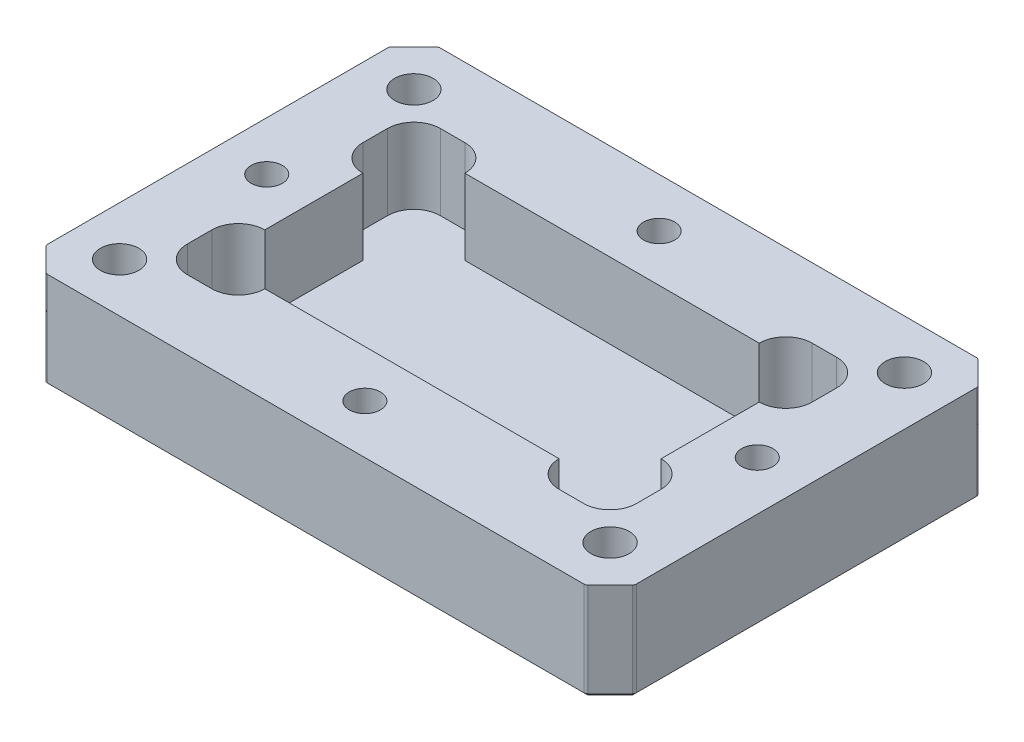
SolidWorks part; units mm, degrees
ref_plane "Front Plane" through (0, 0, 0) normal (0, 0, 1) x (1, 0, 0)
ref_plane "Top Plane" through (0, 0, 0) normal (0, 1, 0) x (1, 0, 0)
ref_plane "Right Plane" through (0, 0, 0) normal (1, 0, 0) x (0, 0, -1)
sketch "Sketch1" plane through (0, 0, 0) normal (0, 1, 0) x (1, 0, 0)
  line L1 (-38.1, 25.4) -> (38.1, 25.4)
  line L2 (-38.1, 25.4) -> (-38.1, -25.4)
  line L3 (-38.1, -25.4) -> (38.1, -25.4)
  line L4 (38.1, 25.4) -> (38.1, -25.4)
  line L5 (-38.1, 25.4) -> (38.1, -25.4) construction
  line L6 (-38.1, -25.4) -> (38.1, 25.4) construction
  point P0 (0, 0)
  dimension "D1" = 76.2
  dimension "D2" = 50.8
extrude "Boss-Extrude1" add sketch "Sketch1" along normal blind 12.7
sketch "Sketch2" plane through (0, 12.7, 0) normal (0, 1, 0) x (1, 0, 0)
  line L1 (-25.654, 12.954) -> (25.654, 12.954)
  line L2 (-25.654, 12.954) -> (-25.654, -12.954)
  line L3 (-25.654, -12.954) -> (25.654, -12.954)
  line L4 (25.654, 12.954) -> (25.654, -12.954)
  line L5 (-25.654, 12.954) -> (25.654, -12.954) construction
  line L6 (-25.654, -12.954) -> (25.654, 12.954) construction
  point P0 (0, 0)
  dimension "D1" = 51.308
  dimension "D2" = 25.908
extrude "Cut-Extrude1" cut sketch "Sketch2" against normal blind 9.779
sketch "Sketch3" plane through (0, 12.7, 0) normal (0, 1, 0) x (1, 0, 0)
  line L0 (25.654, 12.954) -> (-25.654, 12.954) construction
  line L2 (-25.654, 12.954) -> (-25.654, -12.954) construction
  line L3 (-22.479, 16.383) -> (-25.654, 16.383)
  line L4 (-29.083, 12.954) -> (-29.083, 9.779)
  line L6 (-23.2293, 7.3543) -> (-20.0543, 10.5293)
  line L7 (25.654, 12.954) -> (-25.654, 12.954) construction
  arc A0 (-20.0543, 10.5293) -> (-22.479, 16.383) centre (-22.479, 12.954) ccw
  arc A1 (-29.083, 9.779) -> (-23.2293, 7.3543) centre (-25.654, 9.779) ccw
  arc A2 (-25.654, 16.383) -> (-29.083, 12.954) centre (-25.654, 12.954) ccw
  dimension "D1" = 3.429
  dimension "D2" = 3.175
  dimension "D3" = 3.175
extrude "Cut-Extrude2" cut sketch "Sketch3" against normal up to surface (9.779 mm away) up to face at (0, 2.921, 0)
mirror "Mirror1" about plane through (0, 0, 0) normal (0, 0, 1) of "Cut-Extrude2"
mirror "Mirror2" about plane through (0, 0, 0) normal (1, 0, 0) of "Mirror1", "Cut-Extrude2"
hole_wizard "CBORE for #10 Socket Head Cap Screw" positions "Sketch4" profile "Sketch5" counterbore size "#10" standard "ANSI Inch" end condition through all
sketch "Sketch4" plane through (-13.3951, 0, 69.6344) normal (0, -1, 0) x (1, 0, 0)
  point P0 (-18.3549, -50.5844)
  point P2 (45.1451, -50.5844)
  point P4 (45.1451, -88.6844)
  point P6 (-18.3549, -88.6844)
sketch "Sketch5" plane through (-31.75, 0, 19.05) normal (1, 0, 0) x (0, 0, -1)
  line L0 (0, 0) -> (0, 12.7)
  line L1 (0, 12.7) -> (2.4892, 12.7)
  line L2 (2.4892, 12.7) -> (2.4892, 5.08)
  line L3 (2.4892, 5.08) -> (4.445, 5.08)
  line L4 (4.445, 5.08) -> (4.445, 0)
  line L5 (4.445, 0) -> (0, 0)
  line L6 (0, -6.35) -> (0, 107.95) construction
  dimension "Thru Hole Dia." = 4.9784
  dimension "Thru Hole Depth" = 12.7
  dimension "C'Bore Dia." = 8.89
  dimension "C'Bore Depth" = 5.08
chamfer "Chamfer1" distance 3.175 angle 45 4 edges at (38.1, 6.35, 25.4) (38.1, 6.35, -25.4) (-38.1, 6.35, 25.4) (-38.1, 6.35, -25.4)
fillet "Fillet1" radius 0.508 8 edges at (-38.1, 6.35, -22.225) (-34.925, 6.35, -25.4) (34.925, 6.35, -25.4) (38.1, 6.35, -22.225) (38.1, 6.35, 22.225) (34.925, 6.35, 25.4) (-38.1, 6.35, 22.225) (-34.925, 6.35, 25.4)
chamfer "Chamfer2" distance 0.508 angle 45 16 edges at (36.5125, 0, -23.8125) (38.1, 0, 0) (36.5125, 0, 23.8125) (0, 0, 25.4) (-36.5125, 0, 23.8125) (-38.1, 0, 0) (-36.5125, 0, -23.8125) (0, 0, -25.4) (34.909, 0, 25.3613) (-34.909, 0, 25.3613) (38.0613, 0, 22.209) (-38.0613, 0, 22.209) (38.0613, 0, -22.209) (-38.0613, 0, -22.209) (34.909, 0, -25.3613) (-34.909, 0, -25.3613)
hole_wizard "#10-32 Tapped Hole1" positions "Sketch6" profile "Sketch7" tap size "#10-32" standard "ANSI Inch" end condition through all
sketch "Sketch6" plane through (0, 0, 0) normal (0, -1, 0) x (-1, 0, 0)
  line L0 (0, 19.05) -> (0, -19.05)
  line L3 (31.75, 0) -> (-31.75, 0)
  point P0 (-31.75, 0)
  point P2 (31.75, 0)
  point P4 (0, 19.05)
  point P6 (0, -19.05)
  dimension "D1" = 63.5
  dimension "D2" = 38.1
sketch "Sketch7" plane through (31.75, 0, 0) normal (1, 0, 0) x (0, 0, -1)
  line L0 (0, 0) -> (0, 12.7)
  line L1 (0, 12.7) -> (2.0193, 12.7)
  line L2 (2.0193, 12.7) -> (2.0193, 0)
  line L5 (2.0193, 0) -> (0, 0)
  line L11 (0, -6.35) -> (0, 107.95) construction
  dimension "Thru Tap Drill Dia." = 4.0386
  dimension "Thru Tap Drill Depth" = 12.7
cosmetic thread "Hole Thread1" parameters "D2"=4.826
cosmetic thread "Hole Thread2" parameters "D2"=4.826
cosmetic thread "Hole Thread3" parameters "D2"=4.826
cosmetic thread "Hole Thread4" parameters "D2"=4.826
chamfer "Chamfer3" distance 0.508 angle 45 4 edges at (-31.75, 0, -23.495) (-31.75, 0, 14.605) (31.75, 0, 14.605) (31.75, 0, -23.495)
